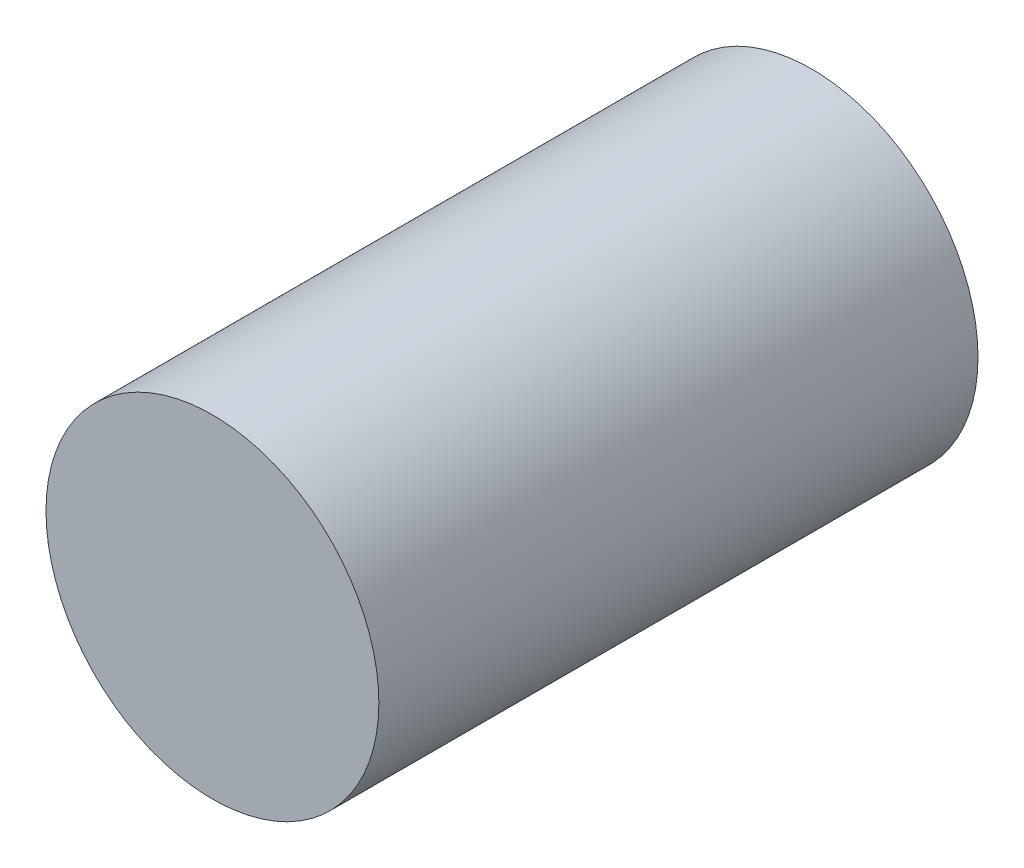
SolidWorks part; units mm, degrees
ref_plane "Front Plane" through (0, 0, 0) normal (0, 0, 1) x (1, 0, 0)
ref_plane "Top Plane" through (0, 0, 0) normal (0, 1, 0) x (1, 0, 0)
ref_plane "Right Plane" through (0, 0, 0) normal (1, 0, 0) x (0, 0, -1)
sketch "Sketch1" plane through (0, 0, 0) normal (0, 0, 1) x (1, 0, 0)
  circle A0 centre (0, 0) radius 3.175
  dimension "D1" = 6.35
extrude "Boss-Extrude1" add sketch "Sketch1" along normal blind 11.43 contours A0
